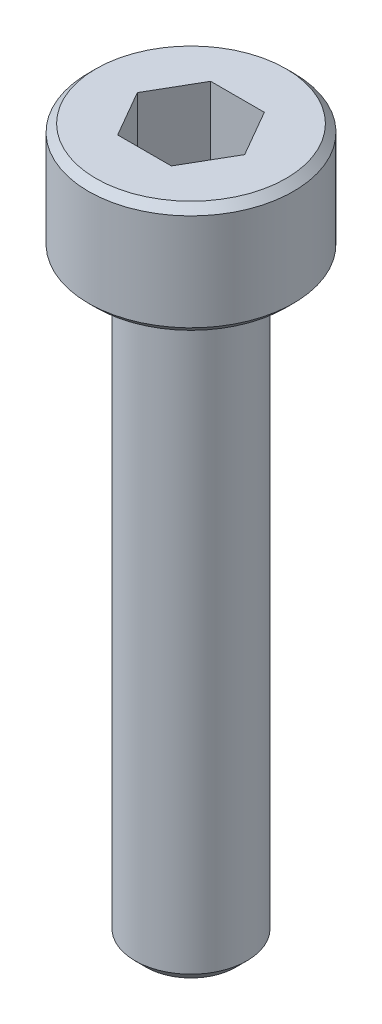
SolidWorks part; units mm, degrees
material "AISI 304"
ref_plane "前视基准面" through (0, 0, 0) normal (0, 0, 1) x (1, 0, 0)
ref_plane "上视基准面" through (0, 0, 0) normal (0, 1, 0) x (1, 0, 0)
ref_plane "右视基准面" through (0, 0, 0) normal (1, 0, 0) x (0, 0, -1)
sketch "草图1" plane through (0, 0, 0) normal (0, 0, 1) x (1, 0, 0)
  line L0 (1.5, 0) -> (2.75, 0)
  line L1 (2.75, 0) -> (2.75, 3)
  line L2 (2.75, 3) -> (0, 3)
  line L3 (0, 3) -> (0, 0)
  line L4 (1.5, 0) -> (1.5, -16)
  line L5 (1.5, -16) -> (0, -16)
  line L6 (0, -16) -> (0, 0)
  dimension "D1" = 3
  dimension "D2" = 2.75
  dimension "D3" = 1.5
  dimension "D4" = 16
  dimension "D5" = 2.75
revolve "旋转1" add sketch "草图1" angle 360 about L3
chamfer "倒角1" distance 0.2 angle 45 2 edges at (0, 0, 2.75) (0, 3, 2.75)
chamfer "倒角2" distance 0.3 angle 45 1 edges at (0, -16, 1.5)
sketch "草图2" plane through (0, 3, 0) normal (0, 1, 0) x (1, 0, 0)
  line L0 (-0.72, 1.2471) -> (0.72, 1.2471)
  line L1 (0.72, 1.2471) -> (1.44, 0)
  line L2 (1.44, 0) -> (0.72, -1.2471)
  line L3 (0.72, -1.2471) -> (-0.72, -1.2471)
  line L4 (-0.72, -1.2471) -> (-1.44, 0)
  line L5 (-1.44, 0) -> (-0.72, 1.2471)
extrude "切除-拉伸1" cut sketch "草图2" against normal blind 2.5
